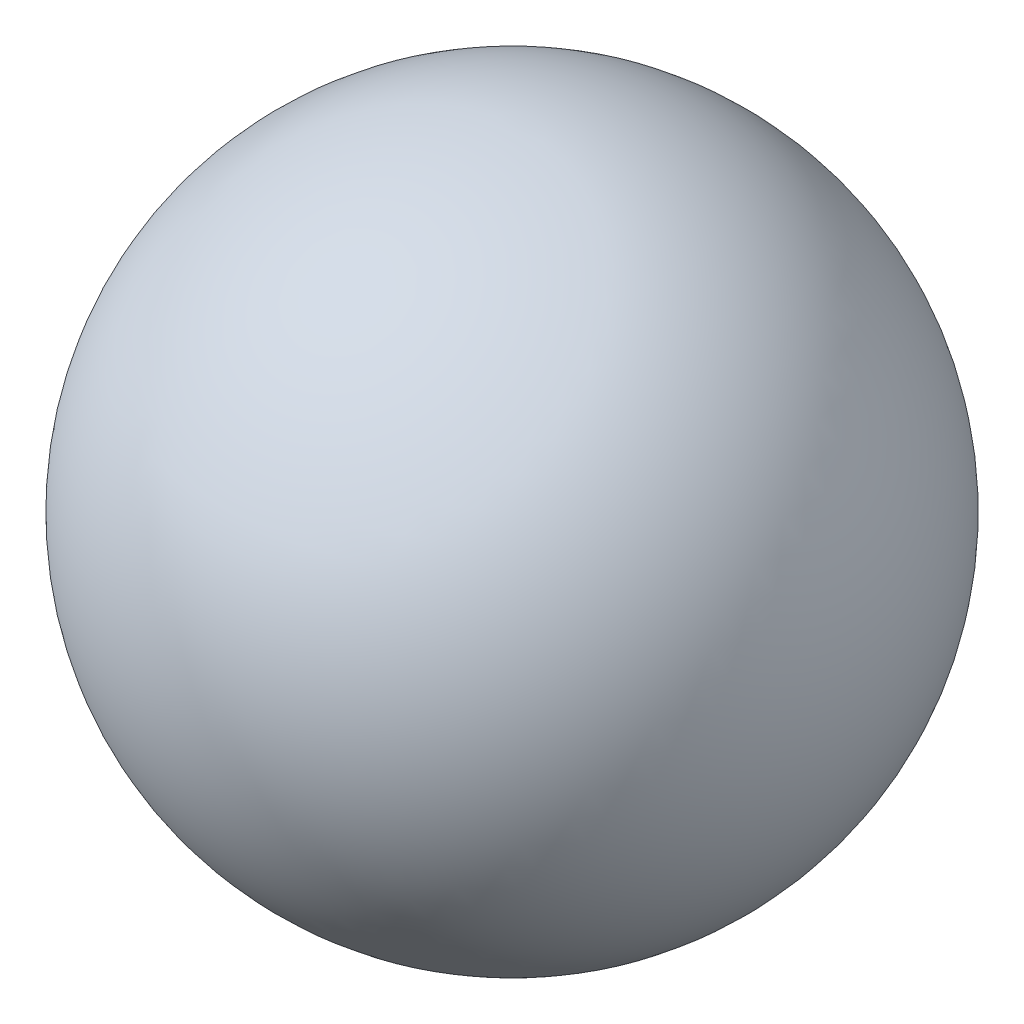
SolidWorks part; units mm, degrees
material "AISI 1045 Acier étiré à froid"
ref_plane "Plan de face" through (0, 0, 0) normal (0, 0, 1) x (1, 0, 0)
ref_plane "Plan de dessus" through (0, 0, 0) normal (0, 1, 0) x (1, 0, 0)
ref_plane "Plan de droite" through (0, 0, 0) normal (1, 0, 0) x (0, 0, -1)
sketch "Esquisse1" plane through (0, 0, 0) normal (0, 0, 1) x (1, 0, 0)
  line L0 (0, 67.3) -> (0, -67.3)
  arc A0 (0, 67.3) -> (0, -67.3) centre (0, 0) ccw
revolve "Révolution1" add sketch "Esquisse1" angle 360 about L0
